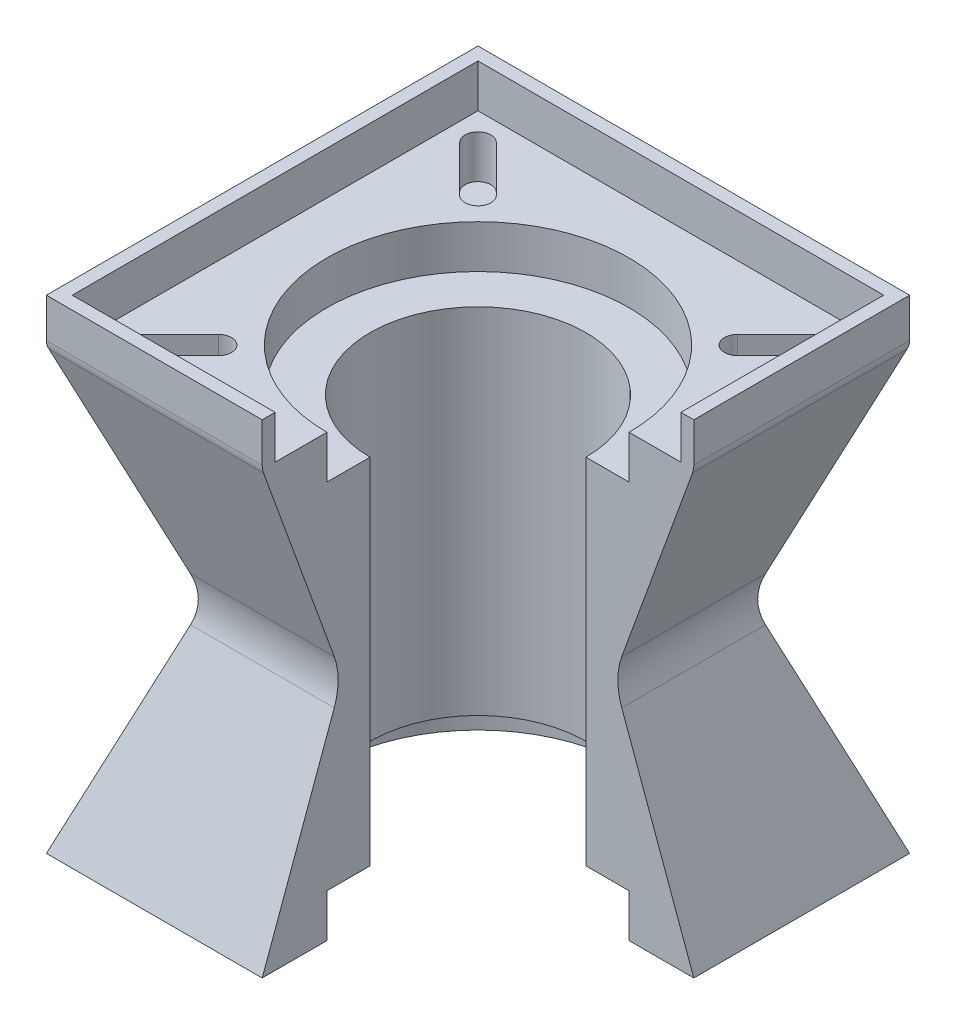
SolidWorks part; units mm, degrees
material "Acier inoxydable moulé"
ref_plane "Plan de face" through (0, 0, 0) normal (0, 0, 1) x (1, 0, 0)
ref_plane "Plan de dessus" through (0, 0, 0) normal (0, 1, 0) x (1, 0, 0)
ref_plane "Plan de droite" through (0, 0, 0) normal (1, 0, 0) x (0, 0, -1)
sketch "Esquisse1" plane through (0, 0, 0) normal (0, 0, 1) x (1, 0, 0)
  line L0 (0, 0) -> (62.875, 0)
  line L1 (62.875, 0) -> (81.4375, 51)
  line L2 (81.4375, 51) -> (-18.5625, 51)
  line L3 (-18.5625, 51) -> (0, 0)
  line L4 (62.875, 0) -> (81.4375, -51)
  line L5 (81.4375, -51) -> (-18.5625, -51)
  line L6 (-18.5625, -51) -> (0, 0)
  dimension "D1" = 100
  dimension "D2" = 51
  dimension "D3" = 290
  dimension "D4" = 290
extrude "Boss.-Extru.1" add sketch "Esquisse1" along normal blind 100 contours L2 L3 L0 L1 | L6 L5 L4 L0
sketch "Esquisse3" plane through (0, 0, 0) normal (1, 0, 0) x (0, 0, -1)
  line L0 (0, -51) -> (-18.5625, 0)
  line L1 (-100, 0) -> (0, 0) construction
  line L2 (-100, -51) -> (-81.4375, 0)
  line L3 (0, -51) -> (0, 0) construction
  line L4 (-100, -51) -> (-100, 0) construction
  line L5 (-100, 51) -> (-81.4375, 0)
  line L6 (0, 51) -> (-18.5625, 0)
  line L7 (-18.5625, 0) -> (0, 0)
  line L8 (0, 0) -> (0, 51)
  line L9 (0, 0) -> (0, -51)
  line L10 (-81.4375, 0) -> (-100, 0)
  line L11 (-100, 0) -> (-100, 51)
  line L12 (-100, 0) -> (-100, -51)
  dimension "D1" = 20
  dimension "D2" = 20
extrude "Enlèv. mat.-Extru.1" cut sketch "Esquisse3" along normal through all both and the other way through all contours L7 L8 L6 | L9 L7 L0 | L11 L10 L5 | L10 L12 L2
sketch "Esquisse4" plane through (0, 51, 0) normal (0, 1, 0) x (1, 0, 0)
  line L0 (-18.5625, 0) -> (31.4375, 0)
  line L1 (81.4375, 0) -> (-18.5625, 0) construction
  line L2 (31.4375, 0) -> (31.4375, -50)
  circle A0 centre (31.4375, -50) radius 25
extrude "Enlèv. mat.-Extru.2" cut sketch "Esquisse4" against normal through all
sketch "Esquisse5" plane through (0, 51, 0) normal (0, 1, 0) x (1, 0, 0)
  circle A1 centre (31.4375, -50) radius 35
extrude "Enlèv. mat.-Extru.3" cut sketch "Esquisse5" against normal blind 10 contours A1
sketch "Esquisse6" plane through (0, 51, 0) normal (0, 1, 0) x (1, 0, 0)
  line L1 (31.4375, -50) -> (86.1633, -50)
  line L2 (31.4375, -50) -> (31.4375, -105.4839)
  line L3 (31.4375, -105.4839) -> (86.1633, -105.4839)
  line L4 (86.1633, -50) -> (86.1633, -105.4839)
extrude "Enlèv. mat.-Extru.4" cut sketch "Esquisse6" against normal through all
fillet "Congé2" radius 15 1 edges at (62.875, 0, 34.2812)
fillet "Congé3" radius 15 3 edges at (31.9189, 0, 18.5625) (0, 0, 50) (15.7188, 0, 81.4375)
sketch "Esquisse8" plane through (0, -51, 0) normal (0, -1, 0) x (1, 0, 0)
  circle A0 centre (31.4375, 50) radius 35
extrude "Enlèv. mat.-Extru.5" cut sketch "Esquisse8" against normal blind 10
sketch "Esquisse9" plane through (0, 51, 0) normal (0, 1, 0) x (1, 0, 0)
  line L2 (31.4375, -100) -> (-18.5625, -100)
  line L3 (-18.5625, -100) -> (-18.5625, 0)
  line L4 (-18.5625, 0) -> (81.4375, 0)
  line L5 (81.4375, 0) -> (81.4375, -50)
  line L7 (-15.5625, -97) -> (-15.5625, -3)
  line L8 (-15.5625, -3) -> (78.4375, -3)
  line L9 (78.4375, -3) -> (78.4375, -47)
  line L12 (28.4375, -97) -> (-15.5625, -97)
  line L15 (28.4375, -87.8814) -> (28.4375, -97) construction
  line L16 (31.4375, -85) -> (31.4375, -100) construction
  line L17 (78.4375, -47) -> (69.3189, -47) construction
  line L18 (81.4375, -50) -> (66.4375, -50) construction
  line L19 (78.4375, -47) -> (78.4375, -50)
  line L20 (81.4375, -50) -> (66.4375, -50) construction
  line L21 (78.4375, -50) -> (81.4375, -50)
  line L22 (28.4375, -97) -> (31.4375, -97)
  line L23 (31.4375, -85) -> (31.4375, -100) construction
  line L24 (31.4375, -96.8387) -> (31.4375, -100)
  line L25 (31.4375, -96.8387) -> (31.4375, -85)
  line L26 (78.4375, -50) -> (66.4375, -50)
  arc A2 (66.4375, -50) -> (31.4375, -85) centre (31.4375, -50) ccw construction
  arc A3 (69.3189, -47) -> (28.4375, -87.8814) centre (31.4375, -50) ccw construction
  arc A7 (31.4375, -85) -> (66.4375, -50) centre (31.4375, -50) cw
  line M3 (-18.5625, -100) -> (31.4375, -100)
  line M4 (31.4375, -100) -> (31.4375, -85)
  line M6 (66.4375, -50) -> (81.4375, -50)
  line M7 (81.4375, -50) -> (81.4375, 0)
  line M8 (81.4375, 0) -> (-18.5625, 0)
  line M9 (-18.5625, 0) -> (-18.5625, -100)
  dimension "D1" = 3
extrude "Boss.-Extru.2" add sketch "Esquisse9" along normal blind 10 contours L22 L12 L7 L8 L9 L19 M6 M7 M8 M9 M3 M4
sketch "Esquisse11" plane through (0, 51, 0) normal (0, 1, 0) x (1, 0, 0)
  line L0 (31.4375, -50) -> (31.4375, 49950) construction
  line L1 (-968.5625, -50) -> (49031.4375, -50) construction
  line L2 (-0.7358, -77.9307) -> (-11.3424, -88.5373)
  line L7 (-0.7358, -22.0693) -> (-11.3424, -11.4627)
  line L8 (-7.0998, -92.78) -> (3.5068, -82.1734)
  line L9 (63.6109, -22.0693) -> (74.2175, -11.4627)
  line L10 (-12.8355, -5.727) -> (-19.3711, 0.8086) construction
  line L11 (69.9748, -7.22) -> (59.3682, -17.8266)
  line L12 (-7.0998, -7.22) -> (3.5068, -17.8266)
  arc A2 (3.5068, -17.8266) -> (-0.7358, -22.0693) centre (1.3855, -19.948) cw
  arc A3 (-11.3424, -11.4627) -> (-7.0998, -7.22) centre (-9.2211, -9.3414) cw
  arc A4 (3.5068, -82.1734) -> (-0.7358, -77.9307) centre (1.3855, -80.052) ccw
  arc A5 (-11.3424, -88.5373) -> (-7.0998, -92.78) centre (-9.2211, -90.6586) ccw
  arc A6 (74.2175, -11.4627) -> (69.9748, -7.22) centre (72.0962, -9.3414) ccw
  arc A7 (59.3682, -17.8266) -> (63.6109, -22.0693) centre (61.4896, -19.948) ccw
  dimension "D2" = 15
  dimension "D3" = 6
extrude "Enlèv. mat.-Extru.7" cut sketch "Esquisse11" against normal blind 10
fillet "Congé5" radius 5 4 edges at (81.4375, 51, 25) (6.4375, 51, 100) (-18.5625, 51, 50) (31.4375, 51, 0)
equation "\"A\"= 102"
equation "\"B\"= 100"
equation "\"C\"= 20"
equation "\"D1@Esquisse1\"=\"B\""
equation "\"A/2\"=51"
equation "\"D2@Esquisse1\"=\"A/2\""
equation "\"D3@Esquisse1\"=\"C\"+270"
equation "\"D4@Esquisse1\"=\"C\"+270"
equation "\"D1@Boss.-Extru.1\"=\"B\""
equation "\"D1@Esquisse3\"=\"C\""
equation "\"D2@Esquisse3\"=\"C\""
